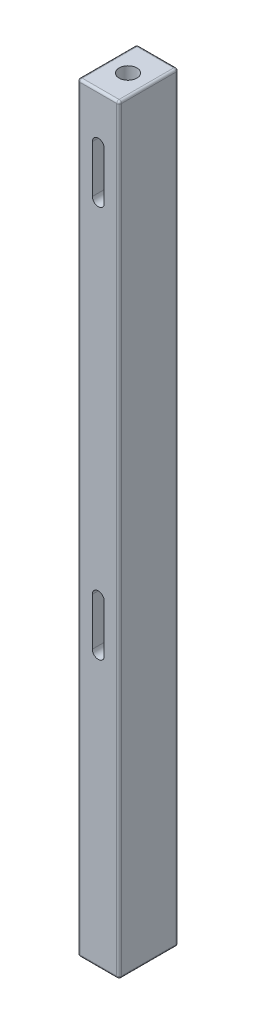
SolidWorks part; units mm, degrees
ref_plane "Front Plane" through (0, 0, 0) normal (0, 0, 1) x (1, 0, 0)
ref_plane "Top Plane" through (0, 0, 0) normal (0, 1, 0) x (1, 0, 0)
ref_plane "Right Plane" through (0, 0, 0) normal (1, 0, 0) x (0, 0, -1)
sketch "Sketch1" plane through (0, 0, 0) normal (0, 1, 0) x (1, 0, 0)
  line L1 (22.225, -31.75) -> (-22.225, -31.75)
  line L2 (22.225, -31.75) -> (22.225, 31.75)
  line L3 (22.225, 31.75) -> (-22.225, 31.75)
  line L4 (-22.225, -31.75) -> (-22.225, 31.75)
  line L5 (22.225, -31.75) -> (-22.225, 31.75) construction
  line L6 (22.225, 31.75) -> (-22.225, -31.75) construction
  point P0 (0, 0)
  dimension "D1" = 44.45
  dimension "D2" = 63.5
extrude "Boss-Extrude1" add sketch "Sketch1" along normal blind 812.8
fillet "Fillet1" radius 2.54 12 edges at (0, 0, 31.75) (22.225, 0, 0) (0, 0, -31.75) (-22.225, 0, 0) (0, 812.8, -31.75) (22.225, 812.8, 0) (0, 812.8, 31.75) (-22.225, 812.8, 0) (-22.225, 406.4, -31.75) (22.225, 406.4, -31.75) (22.225, 406.4, 31.75) (-22.225, 406.4, 31.75)
sketch "Sketch2" plane through (0, 812.8, 0) normal (0, 1, 0) x (1, 0, 0)
  circle A0 centre (0, 0) radius 9.525
  dimension "D1" = 19.05
extrude "Cut-Extrude1" cut sketch "Sketch2" against normal blind 25.4
sketch "Sketch3" plane through (-22.225, 0, 0) normal (-1, 0, 0) x (0, 0, 1)
  line L0 (-9.525, 738.8225) -> (-9.525, 129.2225) construction
  line L1 (-1.5875, 738.8225) -> (-1.5875, 129.2225)
  line L2 (-17.4625, 738.8225) -> (-17.4625, 129.2225)
  line L3 (29.21, 810.26) -> (-29.21, 810.26) construction
  line L4 (-31.75, 2.54) -> (-31.75, 810.26) construction
  arc A0 (-1.5875, 738.8225) -> (-17.4625, 738.8225) centre (-9.525, 738.8225) ccw
  arc A1 (-17.4625, 129.2225) -> (-1.5875, 129.2225) centre (-9.525, 129.2225) ccw
  point P2 (-9.525, 434.0225)
  dimension "D2" = 71.4375
  dimension "D1" = 15.875
  dimension "D3" = 14.2875
  dimension "D4" = 609.6
extrude "Cut-Extrude2" cut sketch "Sketch3" against normal blind 23.495
sketch "Sketch4" plane through (0, 0, 31.75) normal (0, 0, 1) x (1, 0, 0)
  line L0 (0, 342.9) -> (0, 292.1) construction
  line L1 (6.35, 342.9) -> (6.35, 292.1)
  line L2 (-6.35, 342.9) -> (-6.35, 292.1)
  line L3 (0, 762) -> (0, 711.2) construction
  line L4 (6.35, 762) -> (6.35, 711.2)
  line L5 (-6.35, 762) -> (-6.35, 711.2)
  line L6 (-19.685, 812.8) -> (19.685, 812.8) construction
  arc A0 (6.35, 342.9) -> (-6.35, 342.9) centre (0, 342.9) ccw
  arc A1 (-6.35, 292.1) -> (6.35, 292.1) centre (0, 292.1) ccw
  arc A2 (6.35, 762) -> (-6.35, 762) centre (0, 762) ccw
  arc A3 (-6.35, 711.2) -> (6.35, 711.2) centre (0, 711.2) ccw
  point P2 (0, 317.5)
  point P9 (0, 736.6)
  point P17 (0, 812.8)
  dimension "D1" = 12.7
  dimension "D2" = 50.8
  dimension "D3" = 76.2
  dimension "D4" = 495.3
  dimension "D5" = 50.8
  dimension "D6" = 12.7
extrude "Cut-Extrude3" cut sketch "Sketch4" against normal blind 25.4
